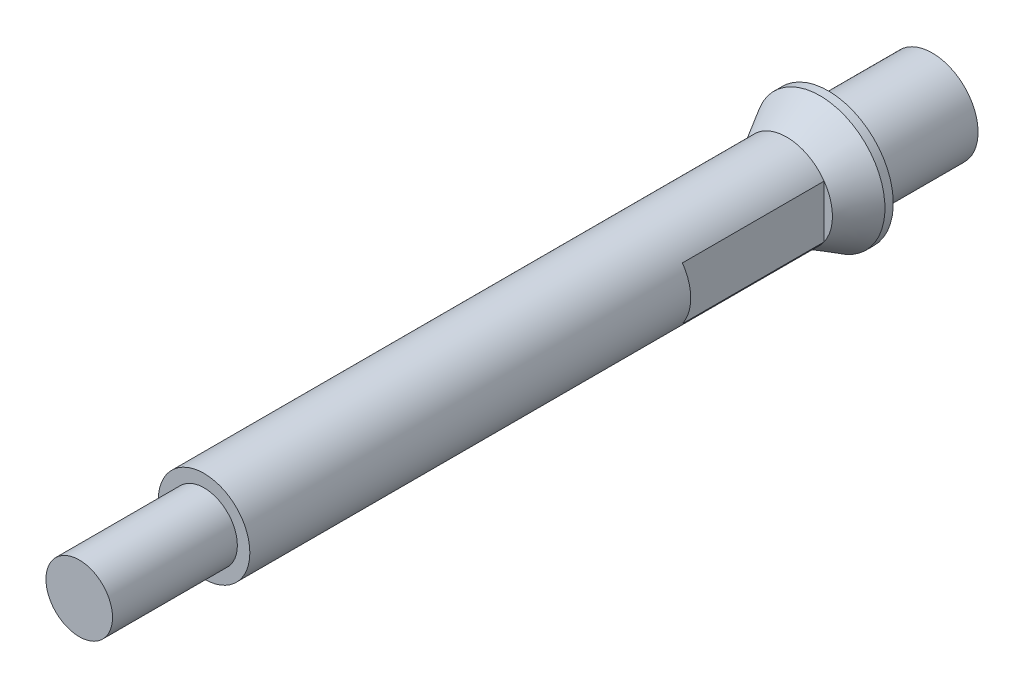
SolidWorks part; units mm, degrees
ref_plane "Front" through (0, 0, 0) normal (0, 0, 1) x (1, 0, 0)
ref_plane "Top" through (0, 0, 0) normal (0, 1, 0) x (1, 0, 0)
ref_plane "Right" through (0, 0, 0) normal (1, 0, 0) x (0, 0, -1)
sketch "Sketch1" plane through (0, 0, 0) normal (0, 0, 1) x (1, 0, 0)
  circle A0 centre (0, 0) radius 11
  dimension "D1" = 22
extrude "Boss-Extrude1" add sketch "Sketch1" along normal blind 140
sketch "Sketch2" plane through (0, 0, 140) normal (0, 0, 1) x (1, 0, 0)
  circle A0 centre (0, 0) radius 8
  dimension "D1" = 16
extrude "Boss-Extrude2" add sketch "Sketch2" along normal blind 30
sketch "Sketch3" plane through (0, 0, 0) normal (0, 0, -1) x (-1, 0, 0)
  circle A2 centre (0, 0) radius 11
  circle A3 centre (0, 0) radius 11
  dimension "D1" = 0
extrude "Boss-Extrude3" add sketch "Sketch3" along normal blind 8 draft 30 draft outward yes
sketch "Sketch4" plane through (0, 0, -8) normal (0, 0, -1) x (-1, 0, 0)
  circle A1 centre (0, 0) radius 15.6188
  circle A2 centre (0, 0) radius 15.6188
  dimension "D1" = 0
extrude "Boss-Extrude4" add sketch "Sketch4" along normal blind 2
ref_plane "Plane1" through (-11, 0, 0) normal (-1, 0, 0) x (0, 0, 1)
sketch "Sketch5" plane through (-11, 0, 0) normal (-1, 0, 0) x (0, 0, 1)
  line L0 (0, 11) -> (0, -11) construction
  line L1 (0, 7.5) -> (34.0532, 7.5)
  line L2 (0, 7.5) -> (0, -7.5)
  line L3 (0, -7.5) -> (34.0532, -7.5)
  line L4 (34.0532, 7.5) -> (34.0532, -7.5)
  dimension "D1" = 15
extrude "Cut-Extrude1" cut sketch "Sketch5" against normal blind 2
mirror "Mirror1" about plane through (0, 0, 0) normal (1, 0, 0) of "Cut-Extrude1"
sketch "Sketch6" plane through (0, 0, -10) normal (0, 0, -1) x (-1, 0, 0)
  circle A0 centre (0, 0) radius 11
  circle A1 centre (0, 0) radius 11 construction
extrude "Boss-Extrude5" add sketch "Sketch6" along normal blind 25
